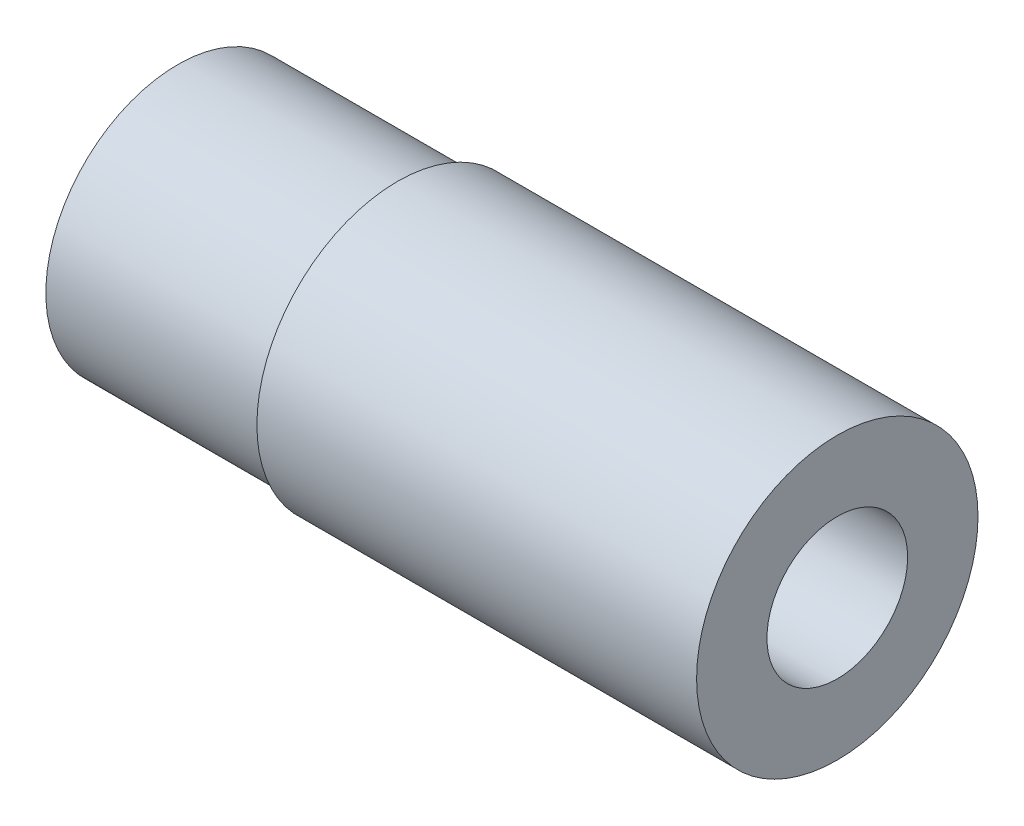
SolidWorks part; units mm, degrees
ref_plane "前视基准面" through (0, 0, 0) normal (0, 0, 1) x (1, 0, 0)
ref_plane "上视基准面" through (0, 0, 0) normal (0, 1, 0) x (1, 0, 0)
ref_plane "右视基准面" through (0, 0, 0) normal (1, 0, 0) x (0, 0, -1)
sketch "草图1" plane through (0, 0, 0) normal (1, 0, 0) x (0, 0, -1)
  circle A0 centre (0, 0) radius 12
  circle A1 centre (0, 0) radius 15
extrude "凸台-拉伸1" add sketch "草图1" along normal blind 25
sketch "草图2" plane through (25, 0, 0) normal (1, 0, 0) x (0, 0, -1)
  circle A0 centre (0, 0) radius 8
  circle A1 centre (0, 0) radius 16
extrude "凸台-拉伸2" add sketch "草图2" along normal blind 50
